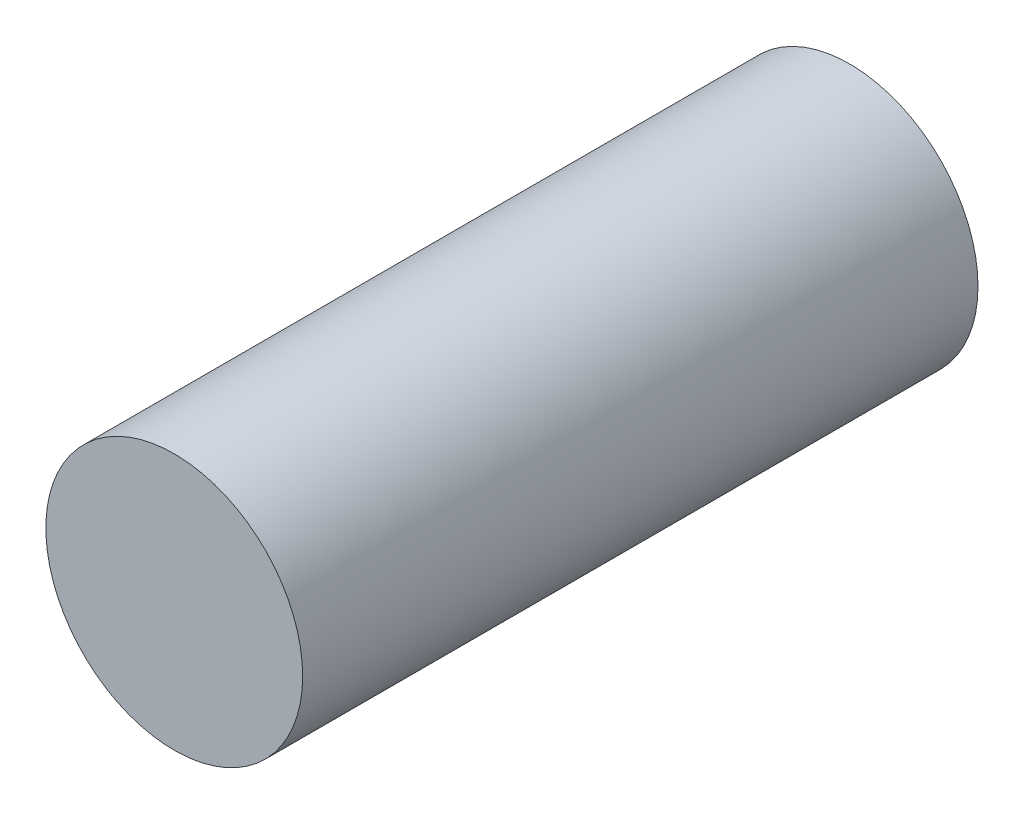
SolidWorks part; units mm, degrees
ref_plane "Front Plane" through (0, 0, 0) normal (0, 0, 1) x (1, 0, 0)
ref_plane "Top Plane" through (0, 0, 0) normal (0, 1, 0) x (1, 0, 0)
ref_plane "Right Plane" through (0, 0, 0) normal (1, 0, 0) x (0, 0, -1)
sketch "Sketch1" plane through (0, 0, 0) normal (0, 0, 1) x (1, 0, 0)
  circle A0 centre (0, 0) radius 1.7145
  dimension "D1" = 3.429
extrude "Boss-Extrude1" add sketch "Sketch1" along normal blind 9.017
